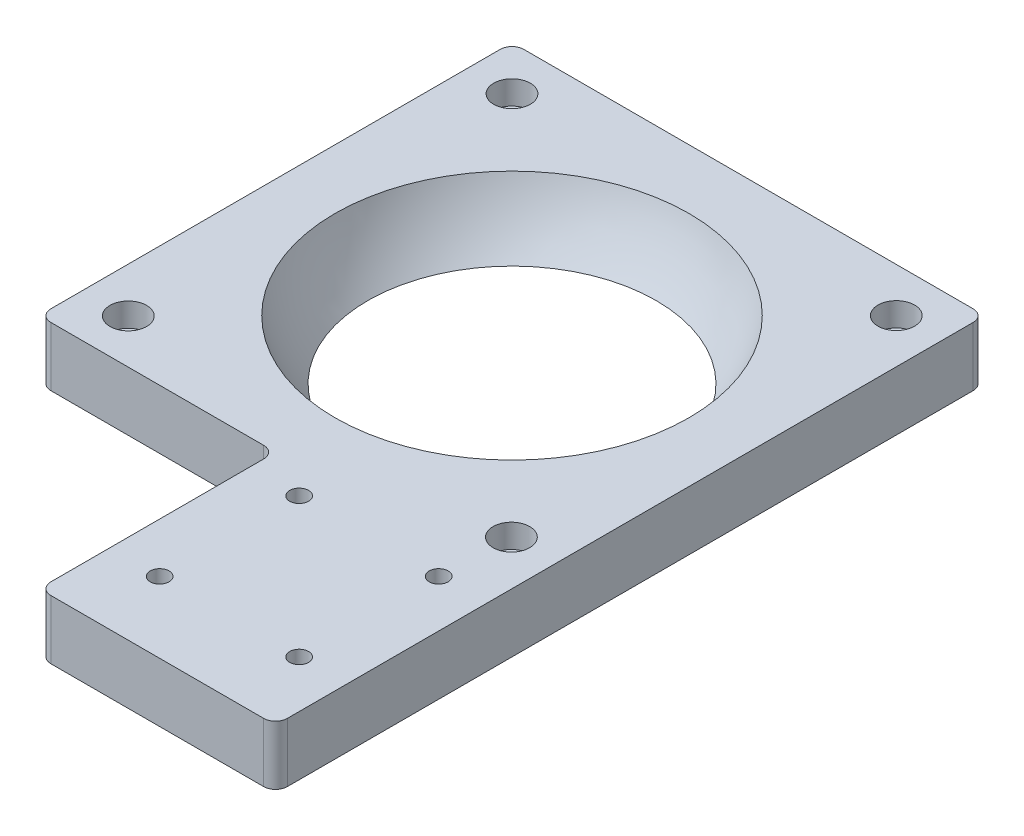
SolidWorks part; units mm, degrees
ref_plane "Front Plane" through (0, 0, 0) normal (0, 0, 1) x (1, 0, 0)
ref_plane "Top Plane" through (0, 0, 0) normal (0, 1, 0) x (1, 0, 0)
ref_plane "Right Plane" through (0, 0, 0) normal (1, 0, 0) x (0, 0, -1)
sketch "Sketch1" plane through (0, 0, 0) normal (0, 1, 0) x (1, 0, 0)
  line L1 (-50.8, -50.8) -> (50.8, -50.8)
  line L2 (-50.8, -50.8) -> (-50.8, 50.8)
  line L3 (-50.8, 50.8) -> (50.8, 50.8)
  line L4 (50.8, -50.8) -> (50.8, 50.8)
  line L5 (-50.8, -50.8) -> (50.8, 50.8) construction
  line L6 (-50.8, 50.8) -> (50.8, -50.8) construction
  point P0 (0, 0)
  dimension "D1" = 101.6
  dimension "D2" = 101.6
extrude "Boss-Extrude1" add sketch "Sketch1" along normal blind 12.7
sketch "Sketch5" plane through (0, 0, 0) normal (0, 0, 1) x (1, 0, 0)
  line L0 (0, 0) -> (30.988, 0)
  line L1 (-50.8, 0) -> (50.8, 0) construction
  line L2 (0, 0) -> (0, 14.478)
  line L3 (0, 14.478) -> (38.608, 14.478)
  arc A0 (30.988, 0) -> (38.608, 14.478) centre (-3.8648, 27.5878) ccw
  dimension "D4" = 44.45
  dimension "D1" = 30.988
  dimension "D2" = 14.478
  dimension "D3" = 38.608
revolve "Cut-Revolve1" cut sketch "Sketch5" angle 360 about L2
sketch "Sketch4" plane through (0, 12.7, 0) normal (0, 1, 0) x (1, 0, 0)
  line L0 (50.8, 50.8) -> (-50.8, 50.8) construction
  line L1 (-41.275, -41.275) -> (41.275, -41.275) construction
  line L2 (-41.275, -41.275) -> (-41.275, 41.275) construction
  line L3 (-41.275, 41.275) -> (41.275, 41.275) construction
  line L4 (41.275, -41.275) -> (41.275, 41.275) construction
  line L5 (-41.275, -41.275) -> (41.275, 41.275) construction
  line L6 (-41.275, 41.275) -> (41.275, -41.275) construction
  line L7 (-50.8, 50.8) -> (-50.8, -50.8) construction
  circle A0 centre (-41.275, 41.275) radius 2.54
  circle A1 centre (41.275, 41.275) radius 2.54
  point P0 (0, 0)
  dimension "D3" = 5.08
  dimension "D4" = 5.08
  dimension "D1" = 9.525
  dimension "D2" = 9.525
extrude "Cut-Extrude3" cut sketch "Sketch4" against normal through all
sketch "Sketch6" plane through (0, 12.7, 0) normal (0, 1, 0) x (1, 0, 0)
  circle A1 centre (-41.275, 41.275) radius 3.937
  circle A2 centre (41.275, 41.275) radius 3.937
  dimension "D2" = 7.874
  dimension "D3" = 7.874
extrude "Cut-Extrude4" cut sketch "Sketch6" against normal blind 5.08
fillet "Fillet2" radius 2.54 4 edges at (-50.8, 6.35, 50.8) (50.8, 6.35, 50.8) (50.8, 6.35, -50.8) (-50.8, 6.35, -50.8)
sketch "Sketch7" plane through (0, 12.7, 0) normal (0, 1, 0) x (1, 0, 0)
  line L9 (-48.26, -50.8) -> (48.26, -50.8) construction
  line L10 (50.8, -101.6) -> (-50.8, -101.6)
  line L11 (50.8, -101.6) -> (50.8, -50.8)
  line L12 (50.8, -50.8) -> (-50.8, -50.8)
  line L13 (-50.8, -101.6) -> (-50.8, -50.8)
  line L14 (50.8, -48.26) -> (50.8, 48.26) construction
  line L15 (-50.8, 48.26) -> (-50.8, -48.26) construction
  line L17 (-50.8, -50.8) -> (50.8, -50.8)
  line L18 (-50.8, -50.8) -> (-50.8, -48.26)
  line L19 (-50.8, -48.26) -> (50.8, -48.26)
  line L20 (50.8, -50.8) -> (50.8, -48.26)
  arc M11 (-50.8, -48.26) -> (-48.26, -50.8) centre (-48.26, -48.26) ccw
  line M12 (-48.26, -50.8) -> (48.26, -50.8)
  arc M13 (48.26, -50.8) -> (50.8, -48.26) centre (48.26, -48.26) ccw
  dimension "D1" = 50.8
extrude "Boss-Extrude2" add sketch "Sketch7" against normal up to surface (12.7 mm away) contours L19 M11 M12 M13 | L13 L10 L11 L12 M12 | L18 L12 M11 | L12 L20 M13 up to face at (-41.275, 0, -38.735)
sketch "Sketch8" plane through (0, 12.7, 0) normal (0, 1, 0) x (1, 0, 0)
  line L1 (-50.8, 48.26) -> (-50.8, -101.6) construction
  line L2 (50.8, -101.6) -> (50.8, 48.26) construction
  circle A0 centre (-41.148, -41.275) radius 3.937
  circle A1 centre (41.148, -41.275) radius 3.937
  circle A2 centre (-41.275, 41.275) radius 2.54 construction
  circle A4 centre (41.275, 41.275) radius 3.937 construction
  dimension "D5" = 7.874
  dimension "D6" = 7.874
  dimension "D4" = 82.55
  dimension "D1" = 82.55
  dimension "D2" = 9.652
  dimension "D3" = 9.652
extrude "Cut-Extrude5" cut sketch "Sketch8" against normal blind 5.08
sketch "Sketch9" plane through (0, 12.7, 0) normal (0, 1, 0) x (1, 0, 0)
  circle A0 centre (-41.148, -41.275) radius 2.54
  circle A1 centre (41.148, -41.275) radius 2.54
  dimension "D1" = 5.08
  dimension "D2" = 5.08
extrude "Cut-Extrude6" cut sketch "Sketch9" against normal through all
fillet "Fillet4" radius 2.54 2 edges at (-50.8, 6.35, 101.6) (50.8, 6.35, 101.6)
sketch "Sketch11" plane through (0, 12.7, 0) normal (0, 1, 0) x (1, 0, 0)
  line L0 (-0.254, -101.6) -> (-0.254, 50.8)
  line L1 (48.26, -101.6) -> (-48.26, -101.6) construction
  line L2 (48.26, 50.8) -> (-48.26, 50.8) construction
  line L3 (50.8, -99.06) -> (50.8, 48.26) construction
  line L4 (8.636, -101.6) -> (8.636, 50.8)
  line L5 (42.672, -101.6) -> (42.672, 50.8)
  line L6 (8.636, -96.266) -> (42.672, -96.266)
  line L7 (42.672, -88.392) -> (8.636, -88.392)
  circle A0 centre (40.64, -86.36) radius 2.032
  circle A1 centre (40.64, -56.388) radius 2.032
  circle A2 centre (10.668, -56.388) radius 2.032
  circle A3 centre (10.668, -86.36) radius 2.032
  dimension "D4" = 5.334
  dimension "D6" = 4.064
  dimension "D7" = 4.064
  dimension "D8" = 4.064
  dimension "D9" = 4.064
  dimension "D1" = 51.054
  dimension "D2" = 8.89
  dimension "D3" = 34.036
  dimension "D5" = 7.874
  dimension "D10" = 29.972
  dimension "D11" = 29.972
extrude "Cut-Extrude7" cut sketch "Sketch11" against normal through all contours A2 | A3 | A0 | A1
sketch "Sketch12" plane through (0, 12.7, 0) normal (0, 1, 0) x (1, 0, 0)
  line L0 (48.26, -101.6) -> (-48.26, -101.6) construction
  line L1 (0, -101.6) -> (-50.8, -101.6)
  line L2 (0, -101.6) -> (0, -50.8)
  line L3 (0, -50.8) -> (-50.8, -50.8)
  line L4 (-50.8, -101.6) -> (-50.8, -50.8)
  line L5 (-50.8, 48.26) -> (-50.8, -99.06) construction
  dimension "D1" = 50.8
  dimension "D2" = 50.8
extrude "Cut-Extrude8" cut sketch "Sketch12" against normal through all
fillet "Fillet5" radius 2.54 3 edges at (0, 6.35, 101.6) (-50.8, 6.35, 50.8) (0, 6.35, 50.8)
